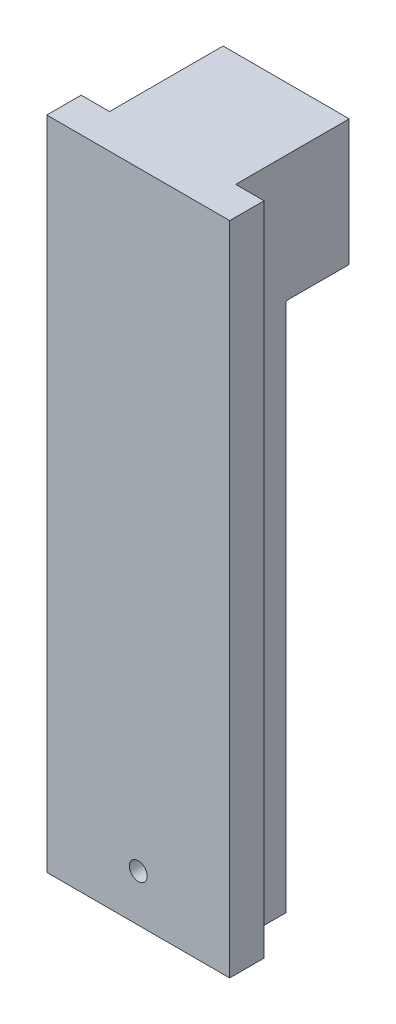
SolidWorks part; units mm, degrees
ref_plane "Płaszczyzna przednia" through (0, 0, 0) normal (0, 0, 1) x (1, 0, 0)
ref_plane "Płaszczyzna górna" through (0, 0, 0) normal (0, 1, 0) x (1, 0, 0)
ref_plane "Płaszczyzna prawa" through (0, 0, 0) normal (1, 0, 0) x (0, 0, -1)
sketch "Szkic1" plane through (0, 0, 0) normal (0, 1, 0) x (1, 0, 0)
  line L0 (0, -6) -> (0, 0) construction
  line L1 (0, 13.45) -> (0, 0) construction
  line L7 (-14.5, 0) -> (14.5, 0)
  line L8 (19, 5.45) -> (10, 5.45) construction
  line L10 (14.5, 0) -> (14.5, 5.45)
  line L11 (14.5, 5.45) -> (10, 5.45)
  line L12 (10, 5.45) -> (10, 13.45)
  line L13 (10, 13.45) -> (-10, 13.45)
  line L14 (-10, 13.45) -> (-10, 5.45)
  line L15 (-10, 5.45) -> (-14.5, 5.45)
  line L16 (-14.5, 5.45) -> (-14.5, 0)
  dimension "D1" = 6
  dimension "D4" = 9
  dimension "D5" = 29
  dimension "D6" = 20
  dimension "D7" = 5.45
  dimension "D8" = 4.5
  dimension "D9" = 29
  dimension "D10" = 20
  dimension "D11" = 20
  dimension "D12" = 8
extrude "Dodanie-wyciągnięcie1" add sketch "Szkic1" along normal blind 104
sketch "Szkic2" plane through (0, 0, -13.45) normal (0, 0, -1) x (-1, 0, 0)
  line L0 (-10, 104) -> (10, 104)
  line L1 (10, 104) -> (10, 84)
  line L2 (10, 104) -> (10, 0) construction
  line L3 (10, 84) -> (-10, 84)
  line L4 (-10, 104) -> (-10, 0) construction
  line L5 (-10, 84) -> (-10, 104)
  dimension "D1" = 20
extrude "Dodanie-wyciągnięcie2" add sketch "Szkic2" along normal blind 10
sketch "Szkic3" plane through (0, 0, -23.45) normal (0, 0, -1) x (-1, 0, 0)
  line L0 (-10, 94) -> (10, 94) construction
  line L1 (-10, 104) -> (-10, 84) construction
  line L2 (10, 84) -> (10, 104) construction
  line L3 (0, 104) -> (0, 84) construction
  line L4 (10, 104) -> (-10, 104) construction
  line L5 (-10, 84) -> (10, 84) construction
  circle A0 centre (0, 94) radius 2.5
  dimension "D1" = 5
extrude "Wytnij-wyciągnięcie1" cut sketch "Szkic3" against normal blind 10
sketch "Szkic4" plane through (0, 0, 0) normal (0, 0, 1) x (1, 0, 0)
  line L0 (0, 0) -> (0, 6) construction
  circle A0 centre (0, 7.425) radius 1.425
  dimension "D2" = 2.85
  dimension "D1" = 6
extrude "Wytnij-wyciągnięcie2" cut sketch "Szkic4" against normal through all
